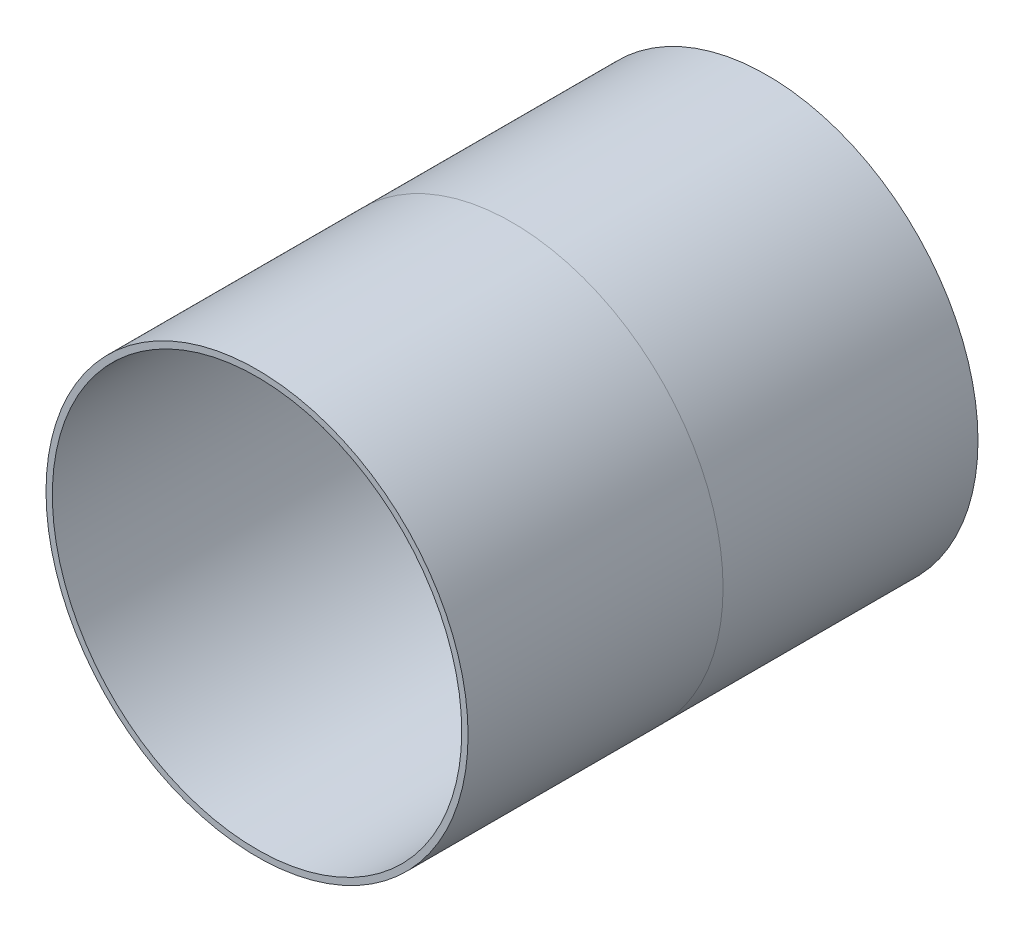
SolidWorks part; units mm, degrees
ref_plane "Plan de face" through (0, 0, 0) normal (0, 0, 1) x (1, 0, 0)
ref_plane "Plan de dessus" through (0, 0, 0) normal (0, 1, 0) x (1, 0, 0)
ref_plane "Plan de droite" through (0, 0, 0) normal (1, 0, 0) x (0, 0, -1)
sketch "Esquisse2" plane through (0, 0, 0) normal (0, 0, 1) x (1, 0, 0)
  circle A0 centre (0, 0) radius 76.1746
  circle A1 centre (0, 0) radius 73.914
  dimension "D1" = 152.3492
  dimension "D2" = 147.828
extrude "Boss.-Extru.1" add sketch "Esquisse2" along normal blind 92.075
sketch "Esquisse3" plane through (0, 0, 92.075) normal (0, 0, 1) x (1, 0, 0)
  circle A0 centre (0, 0) radius 76.2
  circle A1 centre (0, 0) radius 73.914
  dimension "D1" = 147.828
extrude "Boss.-Extru.2" add sketch "Esquisse3" along normal blind 92.075
